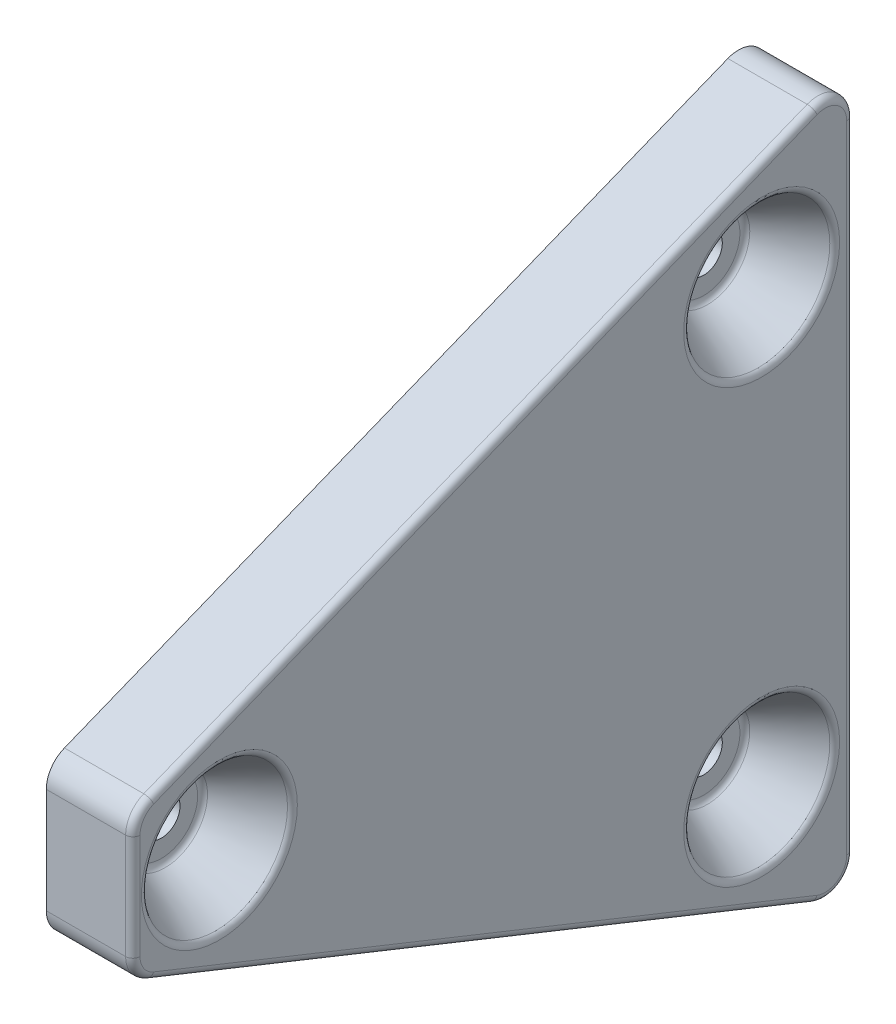
SolidWorks part; units mm, degrees
ref_plane "Front Plane" through (0, 0, 0) normal (0, 0, 1) x (1, 0, 0)
ref_plane "Top Plane" through (0, 0, 0) normal (0, 1, 0) x (1, 0, 0)
ref_plane "Right Plane" through (0, 0, 0) normal (1, 0, 0) x (0, 0, -1)
sketch "Sketch1" plane through (0, 0, 0) normal (1, 0, 0) x (0, 0, -1)
  line L0 (0, 10.3365) -> (0, -2.3635)
  line L1 (0, -2.3635) -> (63.5, -27.7635)
  line L2 (63.5, -27.7635) -> (63.5, 35.7365)
  line L3 (63.5, 35.7365) -> (0, 10.3365)
  line L4 (0, 3.9865) -> (63.5, 3.9865) construction
  point P7 (0, 2.2375)
  point P8 (63.5, 35.7365)
  dimension "D1" = 63.5
  dimension "D2" = 12.7
  dimension "D3" = 63.5
extrude "Boss-Extrude1" add sketch "Sketch1" along normal blind 7.62
sketch "Sketch2" plane through (7.62, 0, 0) normal (1, 0, 0) x (0, 0, -1)
  line L0 (55.372, 32.4853) -> (55.372, -24.5123) construction
  line L1 (63.5, 35.7365) -> (0, 10.3365) construction
  line L2 (0, -2.3635) -> (63.5, -27.7635) construction
  line L3 (63.5, -27.7635) -> (63.5, 35.7365) construction
  line L4 (0, 3.9865) -> (63.5, 3.9865) construction
  line L5 (0, 10.3365) -> (0, -2.3635) construction
  circle A0 centre (55.372, 23.0365) radius 1.6383
  circle A1 centre (7.62, 3.9865) radius 1.6383
  circle A2 centre (55.372, -15.0635) radius 1.6383
  point P20 (58.3844, 21.6863)
  dimension "D2" = 3.2766
  dimension "D3" = 19.05
  dimension "D1" = 8.128
  dimension "D4" = 7.62
extrude "Cut-Extrude1" cut sketch "Sketch2" against normal through all
sketch "Sketch3" plane through (7.62, 0, 0) normal (1, 0, 0) x (0, 0, -1)
  line L0 (0, 3.9865) -> (63.5, 3.9865) construction
  line L1 (0, 10.3365) -> (0, -2.3635) construction
  line L2 (63.5, -27.7635) -> (63.5, 35.7365) construction
  circle A0 centre (7.62, 3.9865) radius 3.556
  circle A6 centre (55.372, 23.0365) radius 3.556
  circle A7 centre (55.372, -15.0635) radius 3.556
  point P0 (7.62, 3.9865)
  point P1 (55.372, 23.0365)
  dimension "D1" = 7.112
extrude "Cut-Extrude2" cut sketch "Sketch3" along normal through all draft 30 from offset 5.1 offset against normal yes
fillet "Fillet1" radius 2.54 4 edges at (3.81, -27.7635, -63.5) (3.81, 35.7365, -63.5) (3.81, -2.3635, 0) (3.81, 10.3365, 0)
fillet "Fillet2" radius 0.635 14 edges at (7.62, 34.0881, -62.384) (7.62, 22.6592, -30.8067) (7.62, 10.0408, -0.4367) (7.62, 3.9865, 0) (7.62, -2.0678, -0.4367) (7.62, -26.1151, -62.384) (7.62, 3.9865, -63.5) (7.62, -14.6862, -30.8067) (7.62, 3.9865, -14.1205) (2.52, 3.9865, -11.176) (2.52, -15.0635, -51.816) (7.62, -15.0635, -48.8715) (7.62, 23.0365, -61.8725) (2.52, 23.0365, -58.928)
